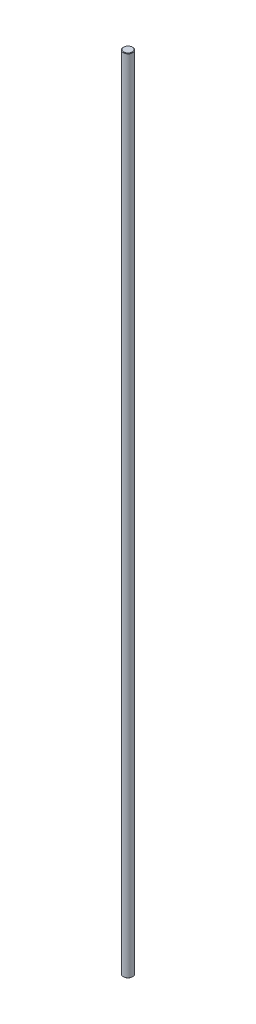
SolidWorks part; units mm, degrees
material "Chromowa stal nierdzewna"
ref_plane "Płaszczyzna przednia" through (0, 0, 0) normal (0, 0, 1) x (1, 0, 0)
ref_plane "Płaszczyzna górna" through (0, 0, 0) normal (0, 1, 0) x (1, 0, 0)
ref_plane "Płaszczyzna prawa" through (0, 0, 0) normal (1, 0, 0) x (0, 0, -1)
sketch "Szkic1" plane through (0, 0, 0) normal (0, 1, 0) x (1, 0, 0)
  circle A0 centre (0, 0) radius 2.5
  dimension "D1" = 5
extrude "Dodanie-wyciągnięcie1" add sketch "Szkic1" along normal blind 423
chamfer "Sfazowanie1" distance 0.25 angle 45 2 edges at (0, 0, 2.5) (0, 423, 2.5)
